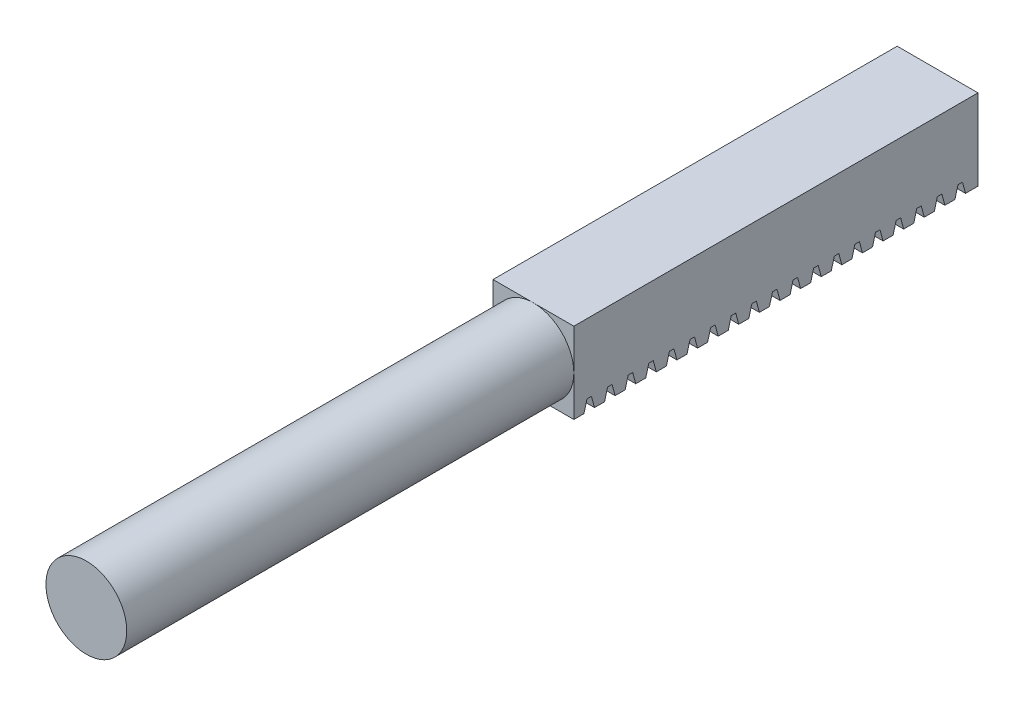
SolidWorks part; units mm, degrees
ref_plane "Planta" through (0, 0, 0) normal (0, 0, 1) x (1, 0, 0)
ref_plane "Alzado" through (0, 0, 0) normal (0, 1, 0) x (1, 0, 0)
ref_plane "Perfil Izquierdo" through (0, 0, 0) normal (1, 0, 0) x (0, 0, -1)
sketch "Croquis1" plane through (0, 0, 0) normal (0, 0, 1) x (1, 0, 0)
  line L0 (4, -4) -> (-4, 4) construction
  line L1 (-4, 4) -> (4, 4)
  line L2 (-4, 4) -> (-4, -4)
  line L3 (-4, -4) -> (4, -4)
  line L4 (4, 4) -> (4, -4)
  dimension "D1" = 8
  dimension "D2" = 8
extrude "Extruir1" add sketch "Croquis1" along normal blind 40
sketch "Croquis4" plane through (4, 0, 0) normal (1, 0, 0) x (0, 0, -1)
  line L0 (-36.96, -4) -> (-36.6612, -2.8849)
  line L1 (-36.96, -4) -> (-35.9172, -4)
  line L2 (-39, -4) -> (-38.7012, -2.8849)
  line L3 (-36.6612, -2.8849) -> (-36.216, -2.8849)
  line L4 (-38.256, -2.8849) -> (-37.9572, -4)
  line L5 (-39, -4) -> (-37.9572, -4)
  line L6 (-40, -4) -> (0, -4) construction
  line L7 (-36.216, -2.8849) -> (-35.9172, -4)
  line L8 (-38.7012, -2.8849) -> (-38.256, -2.8849)
  line L9 (-34.92, -4) -> (-34.6212, -2.8849)
  line L10 (-34.92, -4) -> (-33.8772, -4)
  line L11 (-34.6212, -2.8849) -> (-34.176, -2.8849)
  line L12 (-34.176, -2.8849) -> (-33.8772, -4)
  line L13 (-32.88, -4) -> (-32.5812, -2.8849)
  line L14 (-32.88, -4) -> (-31.8372, -4)
  line L15 (-32.5812, -2.8849) -> (-32.136, -2.8849)
  line L16 (-32.136, -2.8849) -> (-31.8372, -4)
  line L17 (-30.84, -4) -> (-30.5412, -2.8849)
  line L18 (-30.84, -4) -> (-29.7972, -4)
  line L19 (-30.5412, -2.8849) -> (-30.096, -2.8849)
  line L20 (-30.096, -2.8849) -> (-29.7972, -4)
  line L21 (-28.8, -4) -> (-28.5012, -2.8849)
  line L22 (-28.8, -4) -> (-27.7572, -4)
  line L23 (-28.5012, -2.8849) -> (-28.056, -2.8849)
  line L24 (-28.056, -2.8849) -> (-27.7572, -4)
  line L25 (-26.76, -4) -> (-26.4612, -2.8849)
  line L26 (-26.76, -4) -> (-25.7172, -4)
  line L27 (-26.4612, -2.8849) -> (-26.016, -2.8849)
  line L28 (-26.016, -2.8849) -> (-25.7172, -4)
  line L29 (-24.72, -4) -> (-24.4212, -2.8849)
  line L30 (-24.72, -4) -> (-23.6772, -4)
  line L31 (-24.4212, -2.8849) -> (-23.976, -2.8849)
  line L32 (-23.976, -2.8849) -> (-23.6772, -4)
  line L33 (-22.68, -4) -> (-22.3812, -2.8849)
  line L34 (-22.68, -4) -> (-21.6372, -4)
  line L35 (-22.3812, -2.8849) -> (-21.936, -2.8849)
  line L36 (-21.936, -2.8849) -> (-21.6372, -4)
  line L37 (-20.64, -4) -> (-20.3412, -2.8849)
  line L38 (-20.64, -4) -> (-19.5972, -4)
  line L39 (-20.3412, -2.8849) -> (-19.896, -2.8849)
  line L40 (-19.896, -2.8849) -> (-19.5972, -4)
  line L41 (-18.6, -4) -> (-18.3012, -2.8849)
  line L42 (-18.6, -4) -> (-17.5572, -4)
  line L43 (-18.3012, -2.8849) -> (-17.856, -2.8849)
  line L44 (-17.856, -2.8849) -> (-17.5572, -4)
  line L45 (-16.56, -4) -> (-16.2612, -2.8849)
  line L46 (-16.56, -4) -> (-15.5172, -4)
  line L47 (-16.2612, -2.8849) -> (-15.816, -2.8849)
  line L48 (-15.816, -2.8849) -> (-15.5172, -4)
  line L49 (-14.52, -4) -> (-14.2212, -2.8849)
  line L50 (-14.52, -4) -> (-13.4772, -4)
  line L51 (-14.2212, -2.8849) -> (-13.776, -2.8849)
  line L52 (-13.776, -2.8849) -> (-13.4772, -4)
  line L53 (-12.48, -4) -> (-12.1812, -2.8849)
  line L54 (-12.48, -4) -> (-11.4372, -4)
  line L55 (-12.1812, -2.8849) -> (-11.736, -2.8849)
  line L56 (-11.736, -2.8849) -> (-11.4372, -4)
  line L57 (-10.44, -4) -> (-10.1412, -2.8849)
  line L58 (-10.44, -4) -> (-9.3972, -4)
  line L59 (-10.1412, -2.8849) -> (-9.696, -2.8849)
  line L60 (-9.696, -2.8849) -> (-9.3972, -4)
  line L61 (-8.4, -4) -> (-8.1012, -2.8849)
  line L62 (-8.4, -4) -> (-7.3572, -4)
  line L63 (-8.1012, -2.8849) -> (-7.656, -2.8849)
  line L64 (-7.656, -2.8849) -> (-7.3572, -4)
  line L65 (-6.36, -4) -> (-6.0612, -2.8849)
  line L66 (-6.36, -4) -> (-5.3172, -4)
  line L67 (-6.0612, -2.8849) -> (-5.616, -2.8849)
  line L68 (-5.616, -2.8849) -> (-5.3172, -4)
  line L69 (-4.32, -4) -> (-4.0212, -2.8849)
  line L70 (-4.32, -4) -> (-3.2772, -4)
  line L71 (-4.0212, -2.8849) -> (-3.576, -2.8849)
  line L72 (-3.576, -2.8849) -> (-3.2772, -4)
  line L73 (-2.28, -4) -> (-1.9812, -2.8849)
  line L74 (-2.28, -4) -> (-1.2372, -4)
  line L75 (-1.9812, -2.8849) -> (-1.536, -2.8849)
  line L76 (-1.536, -2.8849) -> (-1.2372, -4)
  line L81 (-40, -4) -> (-40, 4) construction
  dimension "D1" = 0.4452
  dimension "D2" = 1.1545
  dimension "D3" = 1.0428
  dimension "D4" = 19
  dimension "D5" = 1
extrude "Cortar-Extruir3" cut sketch "Croquis4" against normal blind 8
sketch "Croquis5" plane through (0, 0, 40) normal (0, 0, 1) x (1, 0, 0)
  circle A0 centre (0, 0) radius 4
extrude "Saliente-Extruir1" add sketch "Croquis5" along normal blind 44.25
